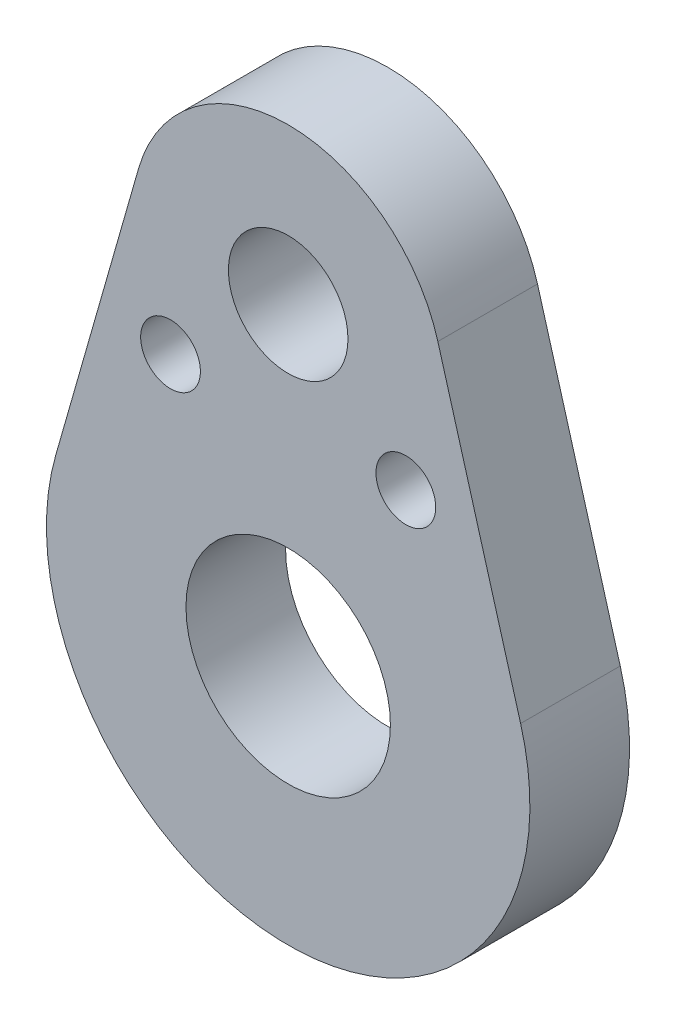
SolidWorks part; units mm, degrees
ref_plane "Plan de face" through (0, 0, 0) normal (0, 0, 1) x (1, 0, 0)
ref_plane "Plan de dessus" through (0, 0, 0) normal (0, 1, 0) x (1, 0, 0)
ref_plane "Plan de droite" through (0, 0, 0) normal (1, 0, 0) x (0, 0, -1)
sketch "Esquisse1" plane through (0, 0, 0) normal (0, 0, 1) x (1, 0, 0)
  line L0 (7.5117, 17.8612) -> (11.6646, 3.3348)
  line L1 (-7.5117, 17.8612) -> (-11.6646, 3.3348)
  line L2 (0, 15.7137) -> (0, 0) construction
  circle A0 centre (0, 0) radius 5.1299
  circle A1 centre (0, 0) radius 12.1319 construction
  circle A2 centre (0, 15.7137) radius 3
  circle A3 centre (0, 15.7137) radius 7.8126 construction
  arc A4 (-7.5117, 17.8612) -> (7.5117, 17.8612) centre (0, 15.7137) cw
  arc A5 (11.6646, 3.3348) -> (-11.6646, 3.3348) centre (0, 0) cw
  circle A6 centre (5.9048, 10.598) radius 1.5
  circle A7 centre (-5.9048, 10.598) radius 1.5
  dimension "D1" = 3
  dimension "D2" = 3
  dimension "D3" = 6
extrude "Boss.-Extru.1" add sketch "Esquisse1" along normal blind 5
